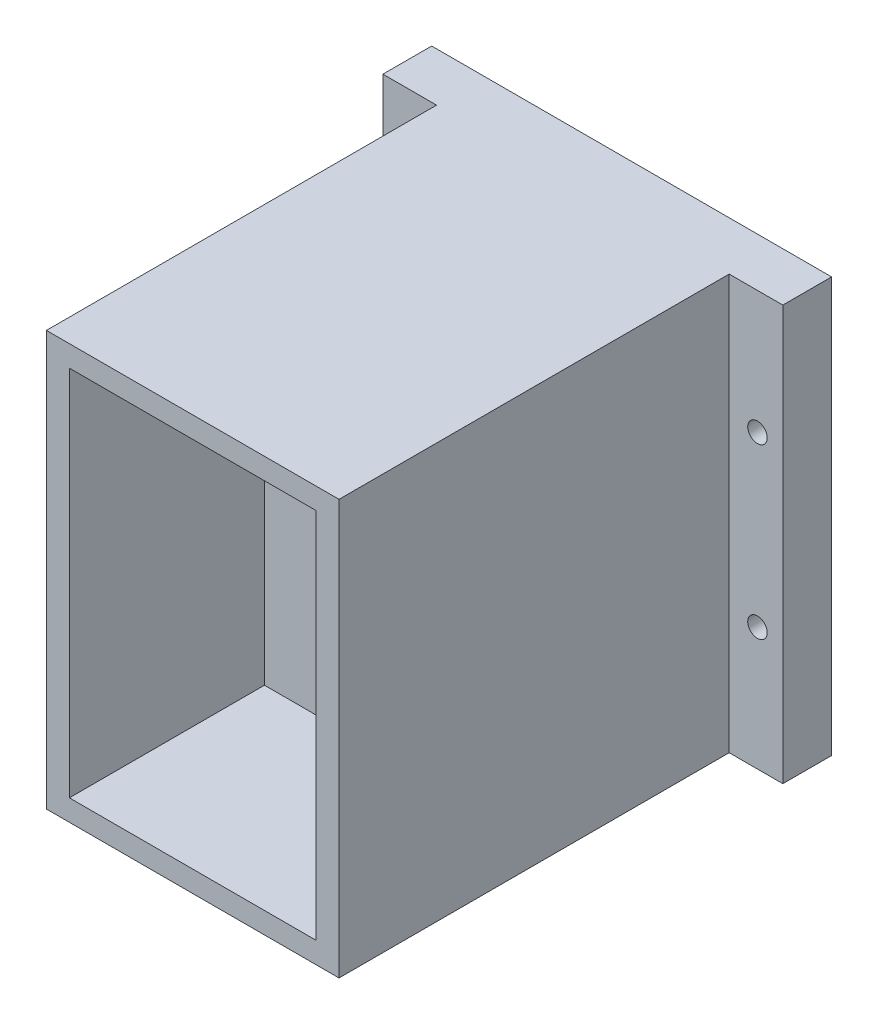
SolidWorks part; units mm, degrees
ref_plane "前视基准面" through (0, 0, 0) normal (0, 0, 1) x (1, 0, 0)
ref_plane "上视基准面" through (0, 0, 0) normal (0, 1, 0) x (1, 0, 0)
ref_plane "右视基准面" through (0, 0, 0) normal (1, 0, 0) x (0, 0, -1)
other "Configuration Table"
sketch "草图1" plane through (0, 0, 0) normal (0, 0, 1) x (1, 0, 0)
  line L1 (15, -21.25) -> (-15, -21.25)
  line L2 (15, -21.25) -> (15, 21.25)
  line L3 (15, 21.25) -> (-15, 21.25)
  line L4 (-15, -21.25) -> (-15, 21.25)
  line L5 (15, -21.25) -> (-15, 21.25) construction
  line L6 (15, 21.25) -> (-15, -21.25) construction
  point P0 (0, 0)
  dimension "D1" = 42.5
  dimension "D2" = 30
extrude "凸台-拉伸1" add sketch "草图1" along normal blind 40
sketch "草图2" plane through (0, 0, 40) normal (0, 0, 1) x (1, 0, 0)
  line L1 (-12.6455, -19.0769) -> (12.6455, -19.0769)
  line L2 (-12.6455, -19.0769) -> (-12.6455, 19.0769)
  line L3 (-12.6455, 19.0769) -> (12.6455, 19.0769)
  line L4 (12.6455, -19.0769) -> (12.6455, 19.0769)
  line L5 (-12.6455, -19.0769) -> (12.6455, 19.0769) construction
  line L6 (-12.6455, 19.0769) -> (12.6455, -19.0769) construction
  point P0 (0, 0)
extrude "切除-拉伸1" cut sketch "草图2" against normal blind 20
sketch "草图3" plane through (0, 0, 0) normal (0, 0, -1) x (-1, 0, 0)
  circle A0 centre (0, 0) radius 10
  dimension "D1" = 20
extrude "切除-拉伸2" cut sketch "草图3" against normal blind 1
sketch "草图4" plane through (0, 0, 0) normal (0, 0, -1) x (-1, 0, 0)
  line L0 (0, 27.6011) -> (0, -25.2758) construction
  line L1 (-20.5, 21.25) -> (20.5, 21.25)
  line L2 (-15, 21.25) -> (15, 21.25) construction
  line L3 (20.5, 21.25) -> (20.5, -21.25)
  line L4 (20.5, -21.25) -> (-20.5, -21.25)
  line L5 (15, -21.25) -> (-15, -21.25) construction
  line L6 (-26.6661, 0) -> (26.5873, 0) construction
  line L7 (-20.5, 21.25) -> (-20.5, -21.25)
  circle A0 centre (17.9, 8.65) radius 1
  circle A1 centre (-17.9, 8.65) radius 1
  circle A2 centre (-17.9, -8.65) radius 1
  circle A3 centre (17.9, -8.65) radius 1
  point P22 (0, -21.25)
  point P23 (0, 21.25)
  dimension "D1" = 35.8
  dimension "D2" = 2
  dimension "D3" = 17.3
  dimension "D4" = 41
extrude "凸台-拉伸2" add sketch "草图4" along normal blind 5
